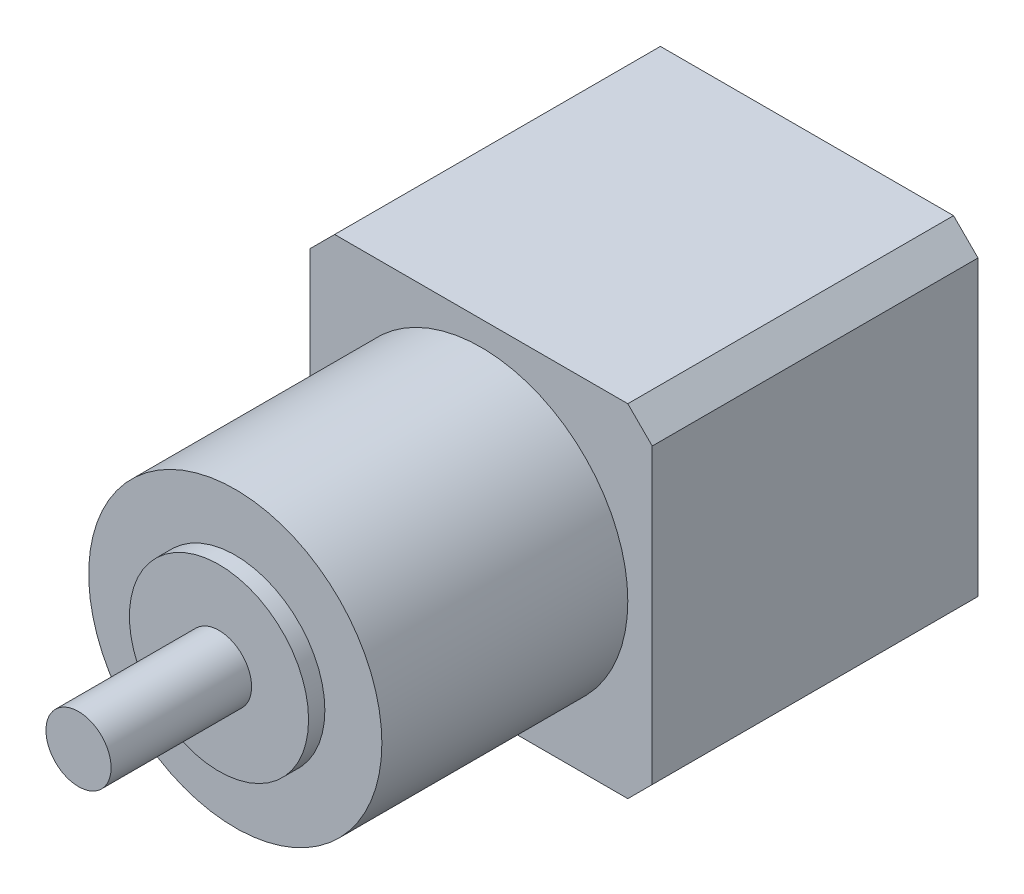
SolidWorks part; units mm, degrees
ref_plane "Front Plane" through (0, 0, 0) normal (0, 0, 1) x (1, 0, 0)
ref_plane "Top Plane" through (0, 0, 0) normal (0, 1, 0) x (1, 0, 0)
ref_plane "Right Plane" through (0, 0, 0) normal (1, 0, 0) x (0, 0, -1)
sketch "Sketch1" plane through (0, 0, 0) normal (0, 0, 1) x (1, 0, 0)
  line L0 (-21, 18) -> (-18, 21)
  line L1 (-18, -21) -> (18, -21)
  line L2 (-21, -18) -> (-21, 18)
  line L3 (-18, 21) -> (18, 21)
  line L4 (21, -18) -> (21, 18)
  line L5 (-21, -21) -> (21, 21) construction
  line L6 (-21, 21) -> (21, -21) construction
  line L7 (-21, -18) -> (-18, -21)
  line L8 (18, -21) -> (21, -18)
  line L9 (18, 21) -> (21, 18)
  point P0 (0, 0)
  dimension "D1" = 42
  dimension "D2" = 42
extrude "Boss-Extrude1" add sketch "Sketch1" along normal blind 40
sketch "Sketch2" plane through (0, 0, 40) normal (0, 0, 1) x (1, 0, 0)
  circle A0 centre (0, 0) radius 18
  dimension "D1" = 36
extrude "Boss-Extrude2" add sketch "Sketch2" along normal blind 30.2
sketch "Sketch3" plane through (0, 0, 70.2) normal (0, 0, 1) x (1, 0, 0)
  circle A0 centre (0, 0) radius 11
  dimension "D1" = 22
extrude "Boss-Extrude3" add sketch "Sketch3" along normal blind 2
sketch "Sketch4" plane through (0, 0, 72.2) normal (0, 0, 1) x (1, 0, 0)
  circle A0 centre (0, 0) radius 4
  dimension "D1" = 8
extrude "Boss-Extrude4" add sketch "Sketch4" along normal blind 17.25
